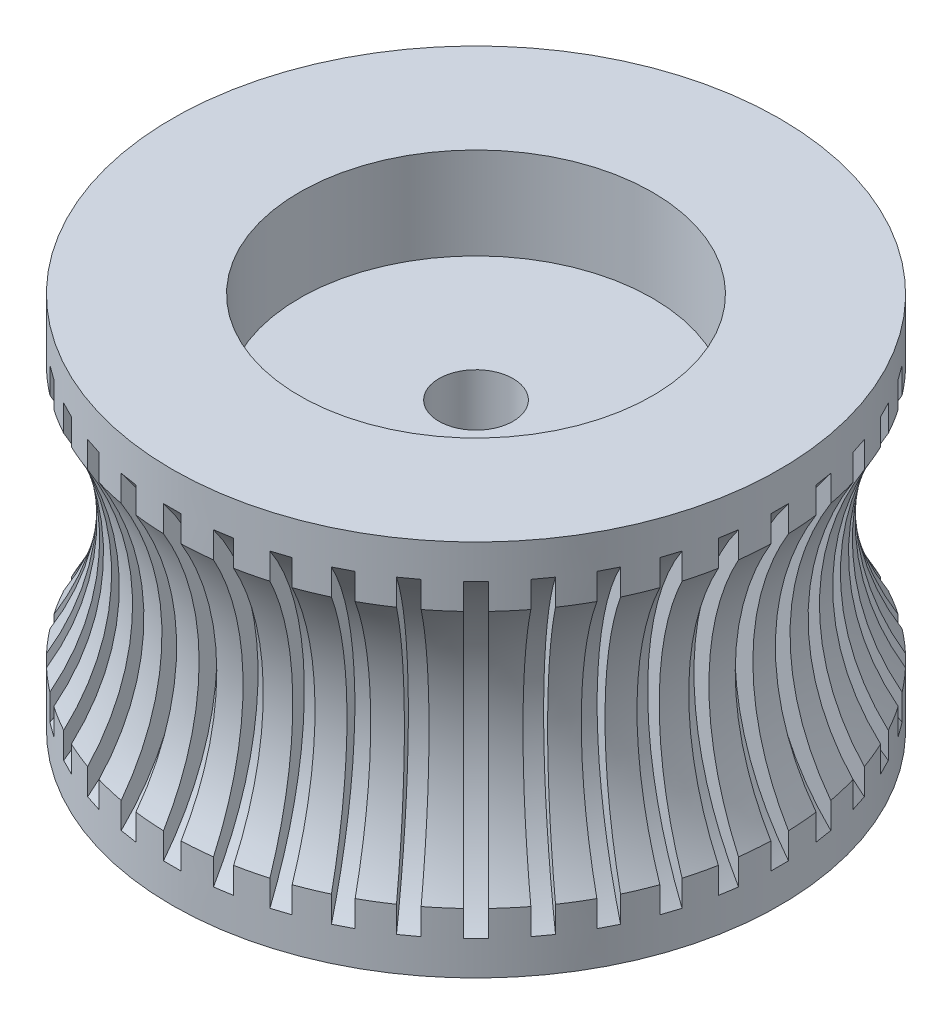
SolidWorks part; units mm, degrees
ref_plane "Front Plane" through (0, 0, 0) normal (0, 0, 1) x (1, 0, 0)
ref_plane "Top Plane" through (0, 0, 0) normal (0, 1, 0) x (1, 0, 0)
ref_plane "Right Plane" through (0, 0, 0) normal (1, 0, 0) x (0, 0, -1)
ref_axis "Axis1" through (0, -14.9479, 0) along (0, 1, 0)
sketch "Sketch1" plane through (0, 0, 0) normal (0, 0, 1) x (1, 0, 0)
  line L0 (2.667, -3.937) -> (2.667, 6.985)
  line L1 (2.667, 6.985) -> (12.7, 6.985)
  line L2 (12.7, 6.985) -> (12.7, 13.589)
  line L3 (12.7, 13.589) -> (21.8676, 13.589)
  line L4 (2.667, -3.937) -> (6.096, -3.937)
  line L5 (6.096, -3.937) -> (6.096, -13.589)
  line L6 (6.096, -13.589) -> (21.8676, -13.589)
  line L7 (21.8676, 13.589) -> (21.8676, 9.2583)
  line L8 (21.8676, -13.589) -> (21.8676, -9.2583)
  line L9 (0, -55) -> (0, 55) construction
  arc A0 (21.8676, 9.2583) -> (21.8676, -9.2583) centre (37.304, 0) ccw
  dimension "D7" = 18
  dimension "D5" = 19.304
  dimension "D1" = 2.667
  dimension "D2" = 6.096
  dimension "D3" = 10.922
  dimension "D4" = 27.178
  dimension "D6" = 9.652
  dimension "D8" = 4.3307
  dimension "D9" = 12.7
revolve "Revolve1" add sketch "Sketch1" angle 360 about axis through (0, -14.9479, 0) along (0, 1, 0)
sketch "Sketch2" plane through (0, 0, 0) normal (1, 0, 0) x (0, 0, -1)
  line L0 (23.7749, 0) -> (-23.7749, 0) construction
  line L1 (0, 14.9479) -> (0, -14.9479) construction
  circle A0 centre (-36, 0) radius 18
  dimension "D1" = 36
  dimension "D2" = 36
extrude "Cut-Extrude1" cut sketch "Sketch2" against normal mid plane 1.27
pattern_circular "CirPattern1" count 40 over 360 about axis through (0, 0, 0) along (0, 1, 0) of "Cut-Extrude1"
